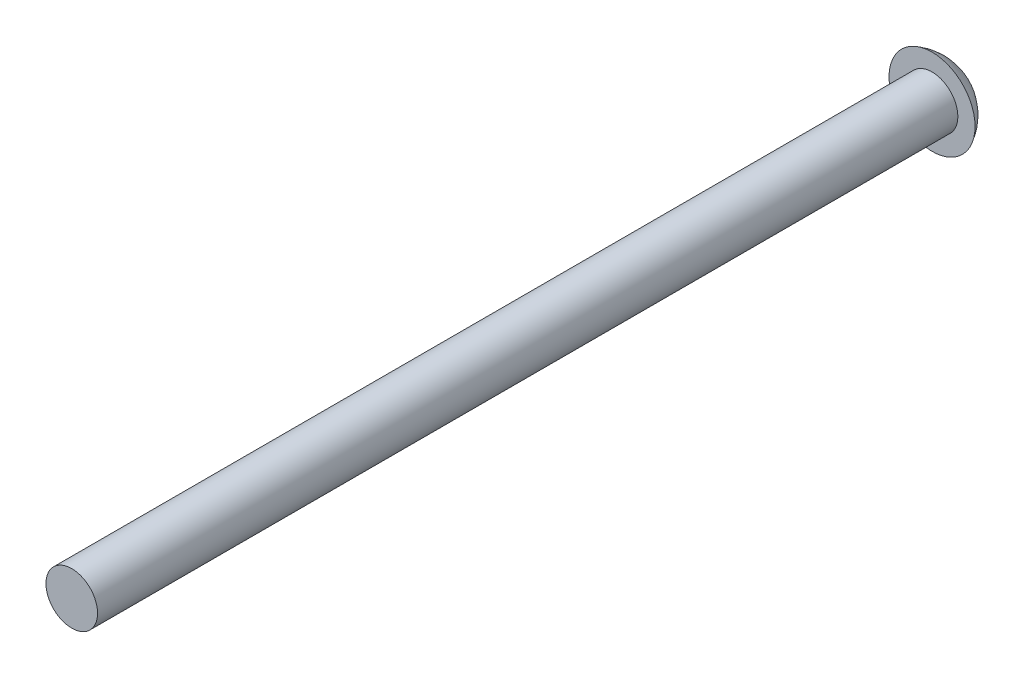
SolidWorks part; units mm, degrees
material "镀铬不锈钢"
ref_plane "前视基准面" through (0, 0, 0) normal (0, 0, 1) x (1, 0, 0)
ref_plane "上视基准面" through (0, 0, 0) normal (0, 1, 0) x (1, 0, 0)
ref_plane "右视基准面" through (0, 0, 0) normal (1, 0, 0) x (0, 0, -1)
sketch "草图1" plane through (0, 0, 0) normal (0, 0, 1) x (1, 0, 0)
  circle A0 centre (0, 0) radius 3
  dimension "D1" = 6
extrude "凸台-拉伸1" add sketch "草图1" along normal blind 100
sketch "草图2" plane through (0, 0, 0) normal (0, 1, 0) x (1, 0, 0)
  line L0 (0, 0) -> (5, 0)
  line L1 (0, 0) -> (0, 3)
  arc A0 (0, 3) -> (5, 0) centre (0, -2.6667) cw
  dimension "D1" = 5
  dimension "D2" = 3
revolve "旋转1" add sketch "草图2" angle 360 about L1
